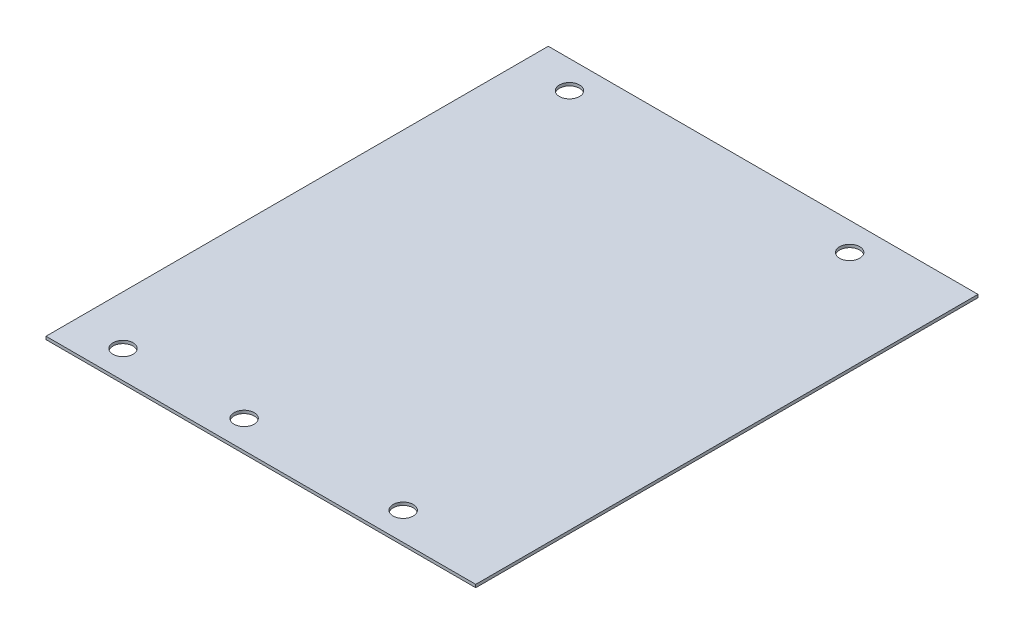
SolidWorks part; units mm, degrees
ref_plane "Alzado" through (0, 0, 0) normal (0, 0, 1) x (1, 0, 0)
ref_plane "Planta" through (0, 0, 0) normal (0, 1, 0) x (1, 0, 0)
ref_plane "Vista lateral" through (0, 0, 0) normal (1, 0, 0) x (0, 0, -1)
sketch "Croquis1" plane through (0, 0, 0) normal (0, 1, 0) x (1, 0, 0)
  line L1 (192.5, -225) -> (-192.5, -225)
  line L2 (192.5, -225) -> (192.5, 225)
  line L3 (192.5, 225) -> (-192.5, 225)
  line L4 (-192.5, -225) -> (-192.5, 225)
  line L5 (192.5, -225) -> (-192.5, 225) construction
  line L6 (192.5, 225) -> (-192.5, -225) construction
  point P0 (0, 0)
  dimension "D1" = 385
  dimension "D2" = 450
extrude "Saliente-Extruir1" add sketch "Croquis1" along normal blind 2.66
sketch "Croquis2" plane through (0, 2.66, 0) normal (0, 1, 0) x (1, 0, 0)
  line L0 (192.5, 225) -> (-192.5, 225) construction
  line L1 (192.5, -225) -> (192.5, 225) construction
  line L2 (-192.5, -225) -> (192.5, -225) construction
  circle A0 centre (-148.5, 200) radius 9
  circle A1 centre (102.5, 200) radius 9
  circle A2 centre (-148.5, -200) radius 9
  circle A3 centre (-40, -200) radius 9
  circle A4 centre (102.5, -200) radius 9
  dimension "D1" = 18
  dimension "D3" = 18
  dimension "D9" = 18
  dimension "D10" = 18
  dimension "D14" = 18
  dimension "D2" = 25
  dimension "D4" = 25
  dimension "D5" = 251
  dimension "D6" = 90
  dimension "D7" = 25
  dimension "D8" = 251
  dimension "D11" = 90
  dimension "D12" = 25
  dimension "D13" = 142.5
  dimension "D15" = 25
extrude "Cortar-Extruir1" cut sketch "Croquis2" against normal blind 3
